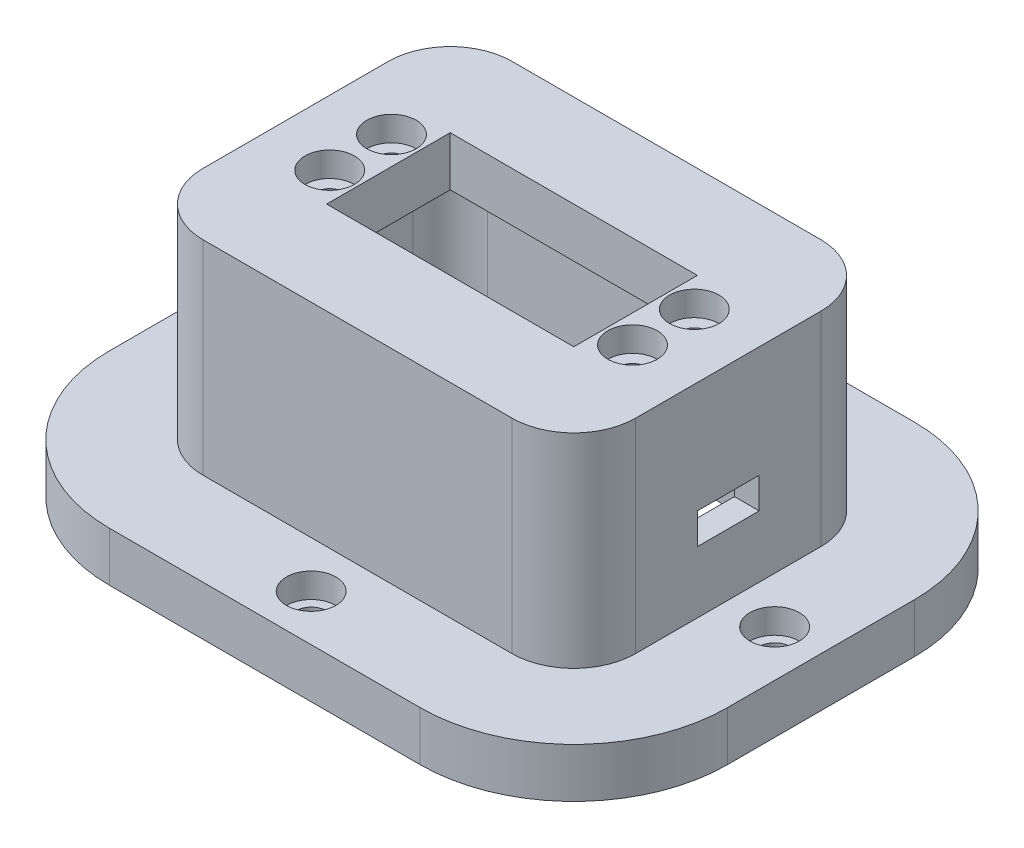
SolidWorks part; units mm, degrees
ref_plane "Alzado" through (0, 0, 0) normal (0, 0, 1) x (1, 0, 0)
ref_plane "Planta" through (0, 0, 0) normal (0, 1, 0) x (1, 0, 0)
ref_plane "Vista lateral" through (0, 0, 0) normal (1, 0, 0) x (0, 0, -1)
sketch "Croquis1" plane through (0, 0, 0) normal (0, 1, 0) x (1, 0, 0)
  line L1 (35, -25) -> (-35, -25)
  line L2 (35, -25) -> (35, 25)
  line L3 (35, 25) -> (-35, 25)
  line L4 (-35, -25) -> (-35, 25)
  line L5 (35, -25) -> (-35, 25) construction
  line L6 (35, 25) -> (-35, -25) construction
  line L8 (-20, -10) -> (20, -10)
  line L9 (-20, -10) -> (-20, 10)
  line L10 (-20, 10) -> (20, 10)
  line L11 (20, -10) -> (20, 10)
  point P0 (0, 0)
  point P12 (20, 0)
  dimension "D1" = 70
  dimension "D2" = 50
  dimension "D3" = 15
  dimension "D4" = 40
  dimension "D5" = 20
  dimension "D6" = 15
extrude "Saliente-Extruir1" add sketch "Croquis1" along normal blind 8
sketch "Croquis2" plane through (0, 8, 0) normal (0, 1, 0) x (1, 0, 0)
  line L0 (20, -10) -> (20, 10) construction
  line L3 (-20, -10) -> (20, -10) construction
  line L4 (20, 0) -> (72.7854, 0) construction
  line L5 (0, 10) -> (0, -10) construction
  line L6 (20, 10) -> (-20, 10) construction
  circle A0 centre (24.5, -5) radius 2
  circle A1 centre (24.5, 5) radius 2
  circle A2 centre (-24.5, -5) radius 2
  circle A3 centre (-24.5, 5) radius 2
  dimension "D3" = 4
  dimension "D1" = 4.5
  dimension "D2" = 5
extrude "Cortar-Extruir1" cut sketch "Croquis2" against normal blind 15
fillet "Redondeo3" radius 10 4 edges at (35, 4, 25) (-35, 4, 25) (-35, 4, -25) (35, 4, -25)
sketch "Croquis3" plane through (0, 0, 0) normal (0, -1, 0) x (1, 0, 0)
  line L0 (-25, 21) -> (25, 21)
  line L1 (-25, 25) -> (25, 25)
  line L2 (-35, 15) -> (-35, -15)
  line L3 (-25, -25) -> (25, -25)
  line L4 (35, 15) -> (35, -15)
  line L5 (31, 15) -> (31, -15)
  line L6 (-25, -21) -> (25, -21)
  line L7 (-31, 15) -> (-31, -15)
  arc A0 (35, 15) -> (25, 25) centre (25, 15) ccw
  arc A1 (35, -15) -> (25, -25) centre (25, -15) cw
  arc A2 (-25, -25) -> (-35, -15) centre (-25, -15) cw
  arc A3 (-35, 15) -> (-25, 25) centre (-25, 15) cw
  arc A4 (31, 15) -> (25, 21) centre (25, 15) ccw
  arc A5 (31, -15) -> (25, -21) centre (25, -15) cw
  arc A6 (-25, -21) -> (-31, -15) centre (-25, -15) cw
  arc A7 (-31, 15) -> (-25, 21) centre (-25, 15) cw
  point P6 (35, 25)
  point P9 (35, -25)
  point P14 (-35, 25)
  dimension "D3" = 10
  dimension "D1" = 70
  dimension "D2" = 50
  dimension "D4" = 4
extrude "Saliente-Extruir2" add sketch "Croquis3" along normal blind 25
sketch "Croquis4" plane through (0, -25, 0) normal (0, -1, 0) x (1, 0, 0)
  line L0 (-25.1526, 40) -> (25.1526, 40)
  line L5 (50, 15.1526) -> (50, -15.1526)
  line L6 (-25.1526, -40) -> (25.1526, -40)
  line L7 (-50, 15.1526) -> (-50, -15.1526)
  line L9 (-25, 21) -> (25, 21)
  line L10 (-31, 15) -> (-31, -15)
  line L11 (-25, -21) -> (25, -21)
  line L12 (31, 15) -> (31, -15)
  arc A4 (25.1526, 40) -> (50, 15.1526) centre (25.1526, 15.1526) cw
  arc A5 (50, -15.1526) -> (25.1526, -40) centre (25.1526, -15.1526) cw
  arc A6 (-25.1526, -40) -> (-50, -15.1526) centre (-25.1526, -15.1526) cw
  arc A7 (-50, 15.1526) -> (-25.1526, 40) centre (-25.1526, 15.1526) cw
  arc A9 (-25, -21) -> (-31, -15) centre (-25, -15) cw
  arc A10 (25, -21) -> (31, -15) centre (25, -15) ccw
  arc A11 (31, 15) -> (25, 21) centre (25, 15) ccw
  arc A12 (-31, 15) -> (-25, 21) centre (-25, 15) cw
  point P6 (35, 25)
  point P9 (35, -25)
  point P10 (31, -21)
  point P13 (31, 21)
  point P14 (-35, 25)
  point P30 (-31, 21)
  dimension "D3" = 6
  dimension "D1" = 62
  dimension "D2" = 42
extrude "Saliente-Extruir3" add sketch "Croquis4" along normal blind 8 separate body
sketch "Croquis5" plane through (0, -25, 0) normal (0, 1, 0) x (1, 0, 0)
  line L0 (-35, 15) -> (-35, -15) construction
  line L3 (-25, 25) -> (25, 25) construction
  line L6 (-11.9487, 0) -> (11.9487, 0) construction
  line L7 (0, 10.9885) -> (0, -12.6955) construction
  circle A0 centre (-42.5, 0) radius 2.5
  circle A1 centre (0, 32.5) radius 2.5
  circle A2 centre (0, -32.5) radius 2.5
  circle A3 centre (42.5, 0) radius 2.5
  dimension "D1" = 7.5
  dimension "D2" = 7.5
  dimension "D3" = 5
  dimension "D4" = 5
extrude "Cortar-Extruir2" cut sketch "Croquis5" against normal blind 10
sketch "Croquis6" plane through (35, 0, 0) normal (1, 0, 0) x (0, 0, -1)
  line L1 (-5, -10) -> (5, -10)
  line L2 (-5, -10) -> (-5, -15)
  line L3 (-5, -15) -> (5, -15)
  line L4 (5, -10) -> (5, -15)
  point P3 (5, -10)
extrude "Cortar-Extruir3" cut sketch "Croquis6" against normal blind 15
sketch "Croquis7" plane through (0, 8, 0) normal (0, 1, 0) x (1, 0, 0)
  line L0 (0, 0) -> (13.9993, 0) construction
  line L1 (0, 0) -> (0, 7.9189) construction
  circle A0 centre (24.5, 5) radius 4
  circle A1 centre (24.5, -5) radius 4
  circle A2 centre (-24.5, -5) radius 4
  circle A3 centre (-24.5, 5) radius 4
  dimension "D1" = 8
extrude "Cortar-Extruir4" cut sketch "Croquis7" against normal blind 4
sketch "Croquis8" plane through (0, -25, 0) normal (0, 1, 0) x (1, 0, 0)
  line L0 (0, 0) -> (11.906, 0) construction
  line L1 (0, 0) -> (0, 7.6477) construction
  circle A0 centre (0, 32.5) radius 4
  circle A1 centre (0, -32.5) radius 4
  circle A2 centre (42.5, 0) radius 4
  circle A3 centre (-42.5, 0) radius 4
  dimension "D1" = 8
  dimension "D2" = 8
extrude "Cortar-Extruir5" cut sketch "Croquis8" against normal blind 4
